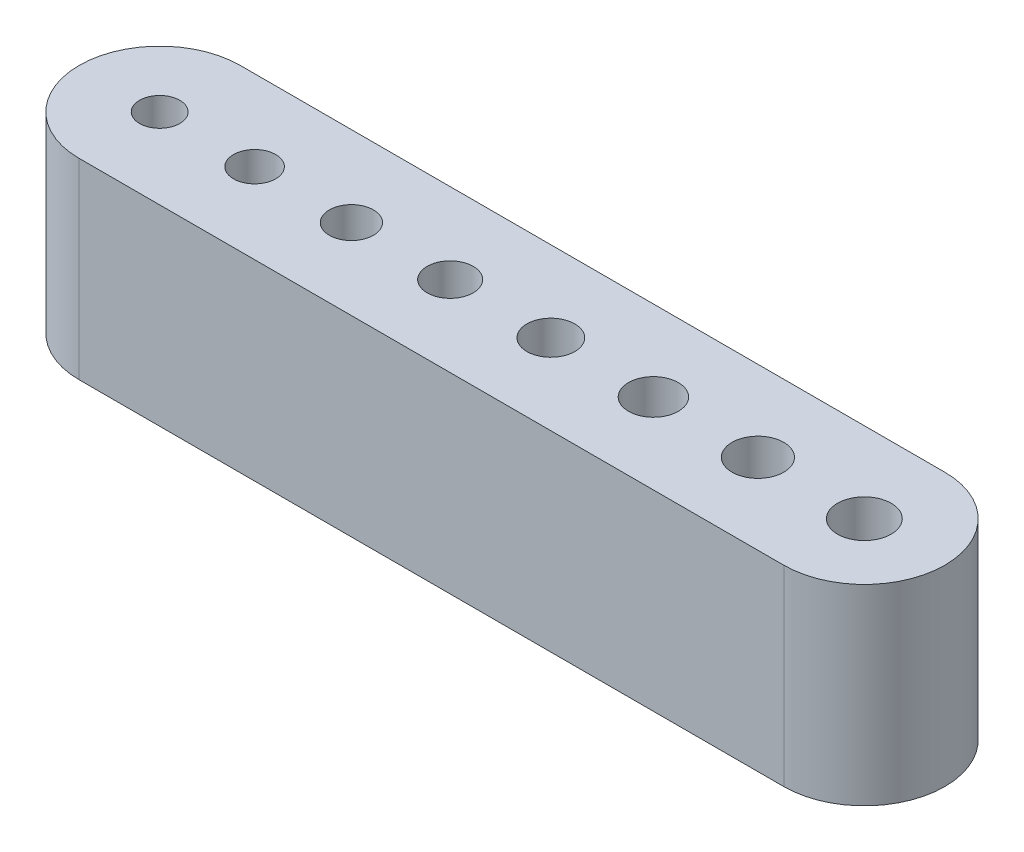
SolidWorks part; units mm, degrees
ref_plane "Front Plane" through (0, 0, 0) normal (0, 0, 1) x (1, 0, 0)
ref_plane "Top Plane" through (0, 0, 0) normal (0, 1, 0) x (1, 0, 0)
ref_plane "Right Plane" through (0, 0, 0) normal (1, 0, 0) x (0, 0, -1)
sketch "Sketch1" plane through (0, 0, 0) normal (0, 1, 0) x (1, 0, 0)
  line L0 (-18.375, 0) -> (18.375, 0) construction
  line L1 (-18.375, 4.2) -> (18.375, 4.2)
  line L2 (-18.375, -4.2) -> (18.375, -4.2)
  line L3 (-17.325, 0) -> (-14.525, 0) construction
  line L4 (-12.325, 0) -> (-9.525, 0) construction
  line L5 (-7.225, 0) -> (-4.425, 0) construction
  line L6 (-2.025, 0) -> (0.775, 0) construction
  line L7 (3.275, 0) -> (6.075, 0) construction
  line L8 (19.775, 0) -> (22.575, 0) construction
  line L10 (8.675, 0) -> (11.475, 0) construction
  line L11 (14.175, 0) -> (16.975, 0) construction
  arc A0 (-18.375, 4.2) -> (-18.375, -4.2) centre (-18.375, 0) ccw
  arc A1 (18.375, -4.2) -> (18.375, 4.2) centre (18.375, 0) ccw
  circle A2 centre (-18.375, 0) radius 1.05
  circle A3 centre (-13.425, 0) radius 1.1
  circle A4 centre (-8.375, 0) radius 1.15
  circle A5 centre (-3.225, 0) radius 1.2
  circle A6 centre (2.025, 0) radius 1.25
  circle A7 centre (18.375, 0) radius 1.4
  circle A8 centre (7.375, 0) radius 1.3
  circle A9 centre (12.825, 0) radius 1.35
  point P2 (0, 0)
  dimension "D1" = 2.1
  dimension "D2" = 2.2
  dimension "D3" = 2.3
  dimension "D4" = 2.4
  dimension "D5" = 2.5
  dimension "D6" = 2.8
  dimension "D7" = 2.6
  dimension "D8" = 2.7
  dimension "D9" = 2.8
extrude "Boss-Extrude1" add sketch "Sketch1" along normal blind 10
